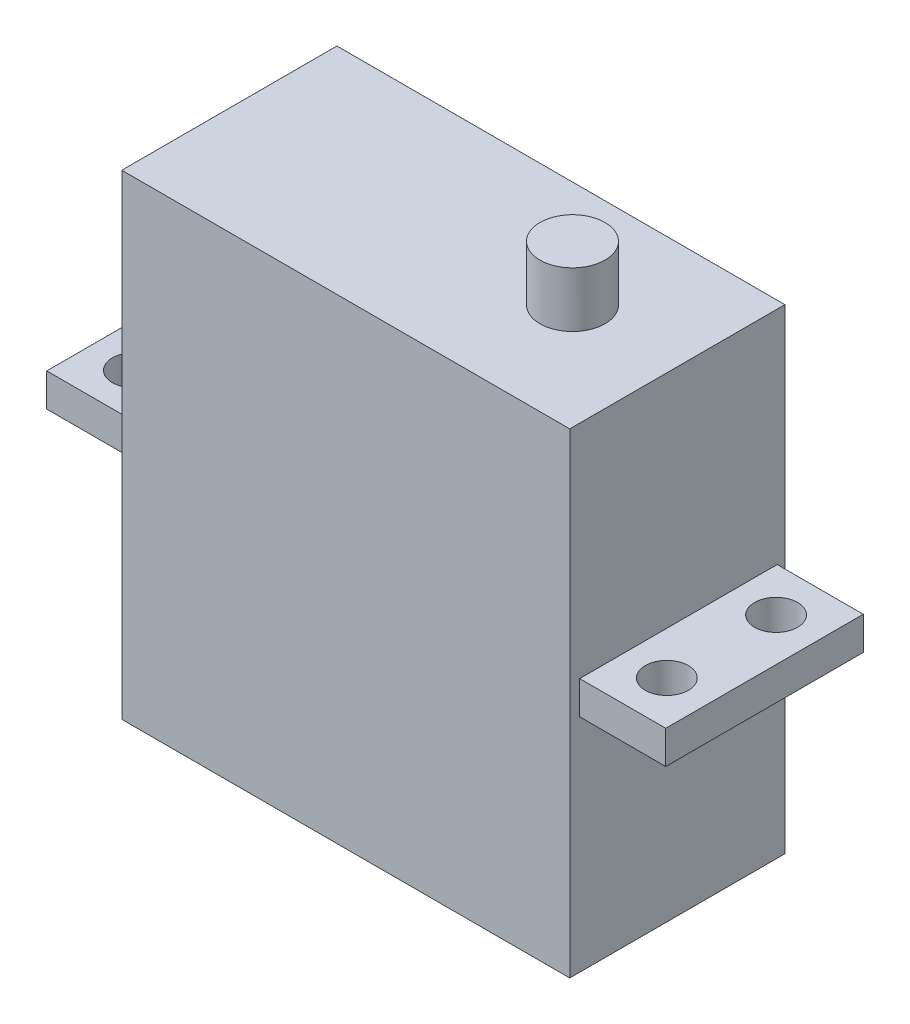
SolidWorks part; units mm, degrees
ref_plane "Alzado" through (0, 0, 0) normal (0, 0, 1) x (1, 0, 0)
ref_plane "Planta" through (0, 0, 0) normal (0, 1, 0) x (1, 0, 0)
ref_plane "Vista lateral" through (0, 0, 0) normal (1, 0, 0) x (0, 0, -1)
sketch "Croquis1" plane through (0, 0, 0) normal (0, 1, 0) x (1, 0, 0)
  line L1 (20.25, -9.85) -> (20.25, 9.65)
  line L2 (-0.05, 0) -> (-0.05, 30.9016) construction
  line L3 (-20.35, -9.85) -> (-20.35, 9.65)
  line L4 (-20.35, 9.65) -> (20.25, 9.65)
  line L5 (20.25, -9.85) -> (-20.35, -9.85)
  dimension "D1" = 40.6
  dimension "D2" = 19.5
extrude "Extruir1" add sketch "Croquis1" along normal mid plane 43.1
sketch "Croquis2" plane through (0, 21.55, 0) normal (0, 1, 0) x (1, 0, 0)
  line L1 (20.25, -9.85) -> (20.25, 9.65) construction
  circle A0 centre (10.6505, -0.003) radius 2.95
  point P0 (20.25, -0.1)
  dimension "D1" = 9.6
  dimension "D2" = 5.9
extrude "Extruir2" add sketch "Croquis2" along normal blind 5
ref_plane "planoservo1" through (10.25, 0, 0) normal (1, 0, 0) x (0, 0, -1)
ref_plane "Plano2" through (0, 0, 0) normal (0, 1, 0) x (-1, 0, 0)
sketch "Croquis4" plane through (0, 0, 0) normal (0, 1, 0) x (-1, 0, 0)
  line L0 (-20.25, -8.95) -> (-20.25, 8.95)
  line L1 (20.25, -8.95) -> (20.25, 8.95)
  line L3 (-28.05, 8.95) -> (-28.05, -8.95)
  line L4 (-28.05, -8.95) -> (-20.25, -8.95)
  line L5 (-28.05, 8.95) -> (-20.25, 8.95)
  line L7 (28.05, 8.95) -> (20.25, 8.95)
  line L8 (28.05, 8.95) -> (28.05, -8.95)
  line L9 (28.05, -8.95) -> (20.25, -8.95)
  circle A0 centre (-24.15, -4.95) radius 1.95
  circle A1 centre (-24.15, 4.95) radius 1.95
  circle A2 centre (24.15, -4.95) radius 1.95
  circle A3 centre (24.15, 4.95) radius 1.95
extrude "Saliente-Extruir1" add sketch "Croquis4" along normal mid plane 3
